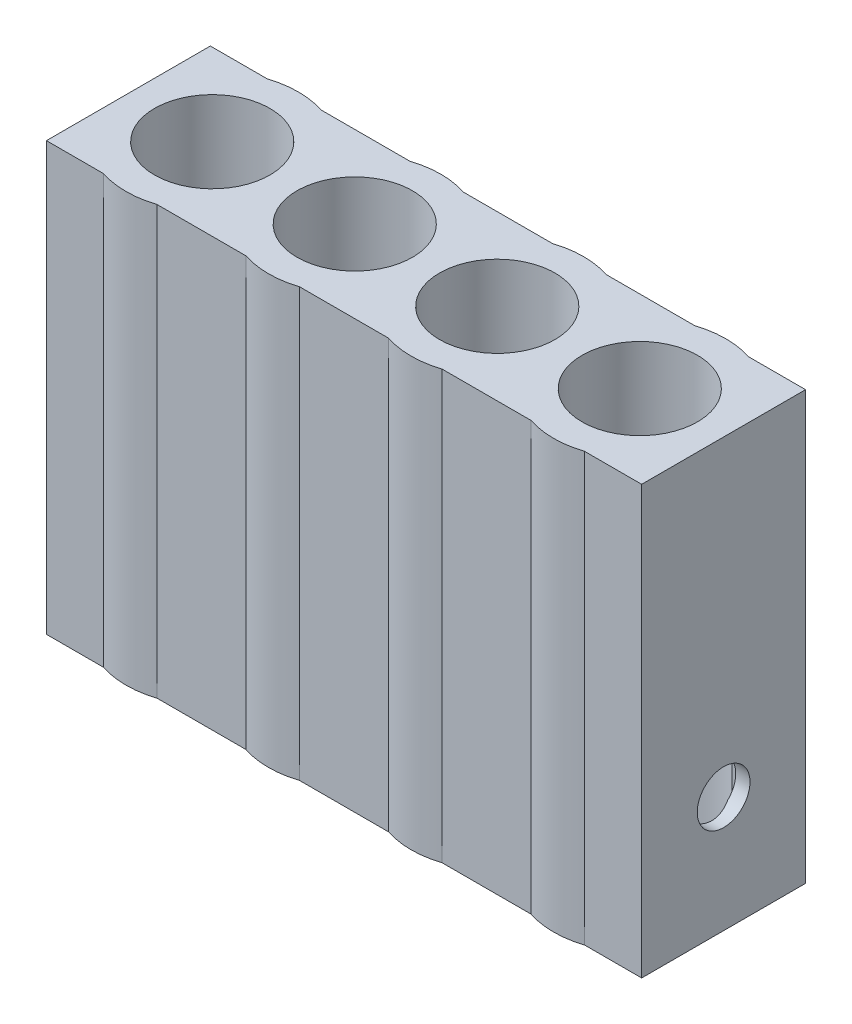
SolidWorks part; units mm, degrees
ref_plane "Front Plane" through (0, 0, 0) normal (0, 0, 1) x (1, 0, 0)
ref_plane "Top Plane" through (0, 0, 0) normal (0, 1, 0) x (1, 0, 0)
ref_plane "Right Plane" through (0, 0, 0) normal (1, 0, 0) x (0, 0, -1)
sketch "Sketch1" plane through (0, 0, 0) normal (0, 1, 0) x (1, 0, 0)
  line L0 (0, 0) -> (100, 0)
  line L1 (100, 0) -> (200, 0)
  line L2 (200, 0) -> (300, 0)
  line L3 (0, 40.5) -> (0, 57.5)
  line L4 (300, 0) -> (300, 57.5)
  line L5 (0, 57.5) -> (300, 57.5)
  line L6 (0, -40.5) -> (0, -57.5)
  line L7 (0, -57.5) -> (300, -57.5)
  line L9 (358.8143, -57.5) -> (-58.8143, -57.5)
  line L10 (358.8143, -57.5) -> (358.8143, 57.5)
  line L11 (358.8143, 57.5) -> (-58.8143, 57.5)
  line L12 (-58.8143, -57.5) -> (-58.8143, 57.5)
  line L13 (150, 57.5) -> (150, -57.5) construction
  line L14 (358.8143, 0) -> (-58.8143, 0) construction
  circle A0 centre (0, 0) radius 40.5
  circle A1 centre (100, 0) radius 40.5
  circle A2 centre (200, 0) radius 40.5
  circle A3 centre (300, 0) radius 40.5
  circle A4 centre (0, 0) radius 60.5
  circle A5 centre (100, 0) radius 60.5
  circle A6 centre (200, 0) radius 60.5
  circle A7 centre (300, 0) radius 60.5
  point P22 (150, 0)
  dimension "D2" = 81
  dimension "D3" = 81
  dimension "D6" = 81
  dimension "D7" = 81
  dimension "D1" = 100
  dimension "D4" = 100
  dimension "D5" = 100
  dimension "D9" = 17
  dimension "D10" = 17
  dimension "D8" = 20
extrude "Boss-Extrude2" add sketch "Sketch1" against normal blind 300 contours A5 A4 L5 L3 A0 | L11 A4 L12 L9 L6 A0 L3 | A5 A0 L6 L7 A4 | A0 A5 A4 A1 L0 | A4 A5 A0 L0 A1 | A6 A1 A4 A5 L7 | A6 A5 L5 A4 A1 | A1 A6 A5 A2 L1 | A5 A6 A1 L1 A2 | A7 A6 L5 A5 A2 | A7 A2 A5 A6 L7 | A2 A7 A6 A3 L2 | A6 A7 A2 L2 A3 | L5 A7 A6 A3 L4 | L9 A7 L10 L11 L4 A3 A6 L7 | A5 A4 L9 | A6 A5 L9 | A7 A6 L9 | A5 L11 A4 | A6 L11 A5 | A7 L11 A6 | A7 L9 L10 | A7 L10 L11 | A4 L11 L12 | A4 L12 L9 | L5 A4 L11 | L5 A5 | L5 A6 | L11 A7 L5 | L7 A7 L9 | L7 A6 | L7 A5 | L9 A4 L7 | L12 A4 | L10 A7
sketch "Sketch2" plane through (0, -300, 0) normal (0, -1, 0) x (1, 0, 0)
  line L188 (-48.8143, 47.5) -> (-48.8143, 12.9387)
  line L189 (-48.8143, -12.9387) -> (-48.8143, -47.5)
  line L190 (-48.8143, -47.5) -> (-17.1464, -47.5)
  line L191 (17.1464, -47.5) -> (82.8536, -47.5)
  line L192 (117.1464, -47.5) -> (182.8536, -47.5)
  line L193 (217.1464, -47.5) -> (282.8536, -47.5)
  line L194 (317.1464, -47.5) -> (348.8143, -47.5)
  line L195 (348.8143, -47.5) -> (348.8143, -12.9387)
  line L196 (348.8143, 12.9387) -> (348.8143, 47.5)
  line L197 (348.8143, 47.5) -> (317.1464, 47.5)
  line L198 (282.8536, 47.5) -> (217.1464, 47.5)
  line L199 (182.8536, 47.5) -> (117.1464, 47.5)
  line L200 (82.8536, 47.5) -> (17.1464, 47.5)
  line L201 (-17.1464, 47.5) -> (-48.8143, 47.5)
  line L202 (-48.8143, 47.5) -> (-48.8143, 12.9387)
  line L203 (-48.8143, -12.9387) -> (-48.8143, -47.5)
  line L204 (-48.8143, -47.5) -> (-17.1464, -47.5)
  line L205 (17.1464, -47.5) -> (82.8536, -47.5)
  line L206 (117.1464, -47.5) -> (182.8536, -47.5)
  line L207 (217.1464, -47.5) -> (282.8536, -47.5)
  line L208 (317.1464, -47.5) -> (348.8143, -47.5)
  line L209 (348.8143, -47.5) -> (348.8143, -12.9387)
  line L210 (348.8143, 12.9387) -> (348.8143, 47.5)
  line L211 (348.8143, 47.5) -> (317.1464, 47.5)
  line L212 (282.8536, 47.5) -> (217.1464, 47.5)
  line L213 (182.8536, 47.5) -> (117.1464, 47.5)
  line L214 (82.8536, 47.5) -> (17.1464, 47.5)
  line L215 (-17.1464, 47.5) -> (-48.8143, 47.5)
  arc A141 (-48.8143, 12.9387) -> (-48.8143, -12.9387) centre (0, 0) ccw
  arc A142 (-17.1464, -47.5) -> (17.1464, -47.5) centre (0, 0) ccw
  arc A143 (82.8536, -47.5) -> (117.1464, -47.5) centre (100, 0) ccw
  arc A144 (182.8536, -47.5) -> (217.1464, -47.5) centre (200, 0) ccw
  arc A145 (282.8536, -47.5) -> (317.1464, -47.5) centre (300, 0) ccw
  arc A146 (348.8143, -12.9387) -> (348.8143, 12.9387) centre (300, 0) ccw
  arc A147 (317.1464, 47.5) -> (282.8536, 47.5) centre (300, 0) ccw
  arc A148 (217.1464, 47.5) -> (182.8536, 47.5) centre (200, 0) ccw
  arc A149 (117.1464, 47.5) -> (82.8536, 47.5) centre (100, 0) ccw
  arc A150 (17.1464, 47.5) -> (-17.1464, 47.5) centre (0, 0) ccw
  arc A151 (-48.8143, 12.9387) -> (-48.8143, -12.9387) centre (0, 0) ccw
  arc A152 (-17.1464, -47.5) -> (17.1464, -47.5) centre (0, 0) ccw
  arc A153 (82.8536, -47.5) -> (117.1464, -47.5) centre (100, 0) ccw
  arc A154 (182.8536, -47.5) -> (217.1464, -47.5) centre (200, 0) ccw
  arc A155 (282.8536, -47.5) -> (317.1464, -47.5) centre (300, 0) ccw
  arc A156 (348.8143, -12.9387) -> (348.8143, 12.9387) centre (300, 0) ccw
  arc A157 (317.1464, 47.5) -> (282.8536, 47.5) centre (300, 0) ccw
  arc A158 (217.1464, 47.5) -> (182.8536, 47.5) centre (200, 0) ccw
  arc A159 (117.1464, 47.5) -> (82.8536, 47.5) centre (100, 0) ccw
  arc A160 (17.1464, 47.5) -> (-17.1464, 47.5) centre (0, 0) ccw
  dimension "D1" = 10
extrude "Cut-Extrude1" cut sketch "Sketch2" against normal blind 200
sketch "Sketch4" plane through (-58.8143, 0, 0) normal (-1, 0, 0) x (0, 0, 1)
  circle A0 centre (0, -218.855) radius 18.503
  dimension "D1" = 37.006
extrude "Cut-Extrude2" cut sketch "Sketch4" against normal mid plane 1000 contours A0
sketch "Sketch5" plane through (0, 0, 0) normal (0, 1, 0) x (1, 0, 0)
  line L0 (358.8143, 14.1818) -> (358.8143, -14.1818)
  line L1 (-58.8143, 14.1818) -> (-58.8143, -14.1818)
sketch "Sketch8" plane through (0, 0, 0) normal (0, 1, 0) x (1, 0, 0)
  line L1 (-58.8143, 14.1818) -> (358.8143, 14.1818)
  line L2 (-58.8143, 14.1818) -> (-58.8143, -14.1818)
  line L3 (-58.8143, -14.1818) -> (358.8143, -14.1818)
  line L4 (358.8143, 14.1818) -> (358.8143, -14.1818)
  arc M9 (358.8143, -14.1818) -> (358.8143, 14.1818) centre (300, 0) ccw
  arc M21 (-58.8143, 14.1818) -> (-58.8143, -14.1818) centre (0, 0) ccw
extrude "Cut-Extrude3" cut sketch "Sketch8" against normal blind 300 contours L2 M21 | L4 M9
